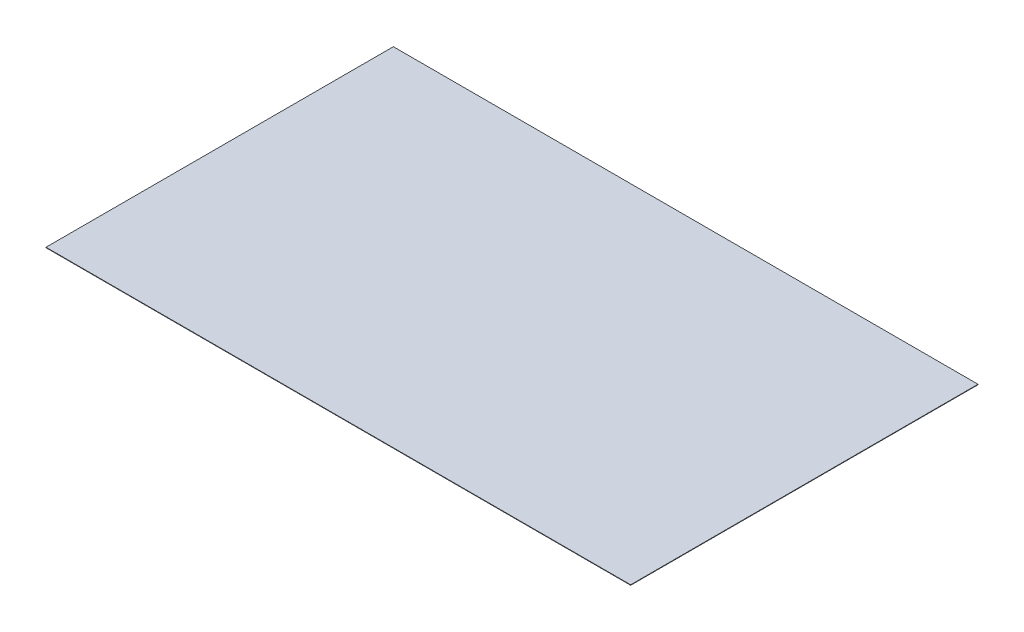
SolidWorks part; units mm, degrees
ref_plane "Front Plane" through (0, 0, 0) normal (0, 0, 1) x (1, 0, 0)
ref_plane "Top Plane" through (0, 0, 0) normal (0, 1, 0) x (1, 0, 0)
ref_plane "Right Plane" through (0, 0, 0) normal (1, 0, 0) x (0, 0, -1)
other "Configuration Table"
sketch "Sketch1" plane through (0, 0, 0) normal (0, 0, 1) x (1, 0, 0)
  line L1 (62.5, 765) -> (1337.5, 765)
  line L2 (62.5, 765) -> (62.5, 766)
  line L3 (62.5, 766) -> (1337.5, 766)
  line L4 (1337.5, 765) -> (1337.5, 766)
extrude "STORE_ayirici_sac_ust_1" add sketch "Sketch1" against normal blind 757.5 separate body
